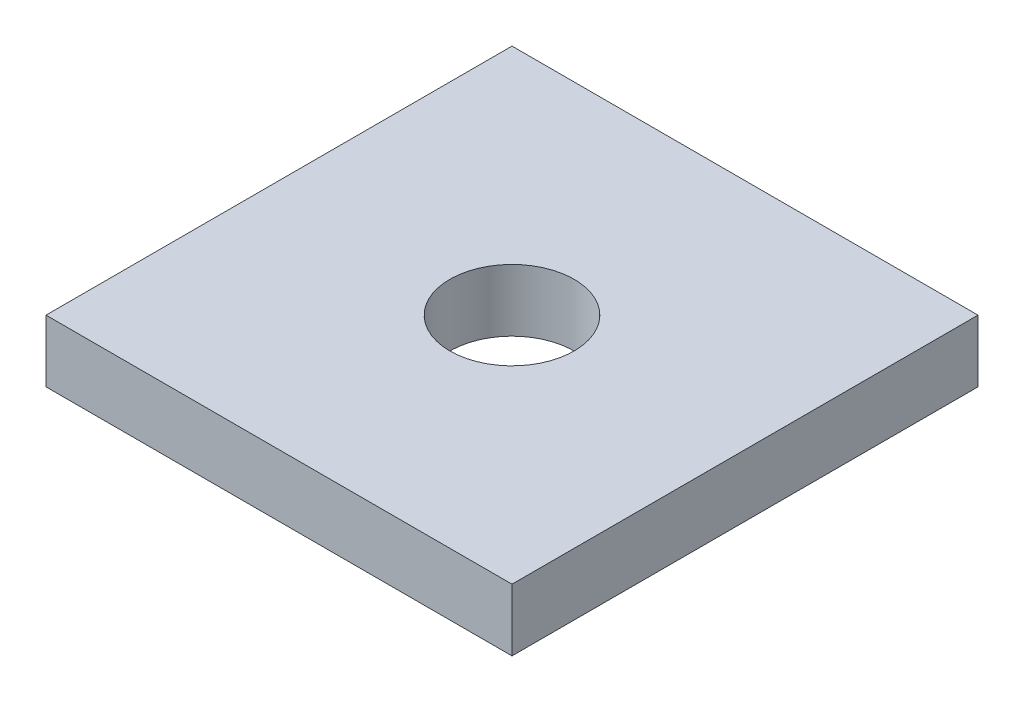
SolidWorks part; units mm, degrees
ref_plane "Front Plane" through (0, 0, 0) normal (0, 0, 1) x (1, 0, 0)
ref_plane "Top Plane" through (0, 0, 0) normal (0, 1, 0) x (1, 0, 0)
ref_plane "Right Plane" through (0, 0, 0) normal (1, 0, 0) x (0, 0, -1)
sketch "Sketch1" plane through (0, 0, 0) normal (0, 1, 0) x (1, 0, 0)
  line L1 (-19.05, -19.05) -> (19.05, -19.05)
  line L2 (-19.05, -19.05) -> (-19.05, 19.05)
  line L3 (-19.05, 19.05) -> (19.05, 19.05)
  line L4 (19.05, -19.05) -> (19.05, 19.05)
  line L5 (-19.05, -19.05) -> (19.05, 19.05) construction
  line L6 (-19.05, 19.05) -> (19.05, -19.05) construction
  point P0 (0, 0)
  dimension "D1" = 38.1
  dimension "1.5" = 38.1
extrude "Boss-Extrude1" add sketch "Sketch1" along normal blind 5.08
sketch "Sketch2" plane through (0, 5.08, 0) normal (0, 1, 0) x (1, 0, 0)
  circle A2 centre (0, 0) radius 5.08
extrude "Cut-Extrude1" cut sketch "Sketch2" against normal blind 5.08
